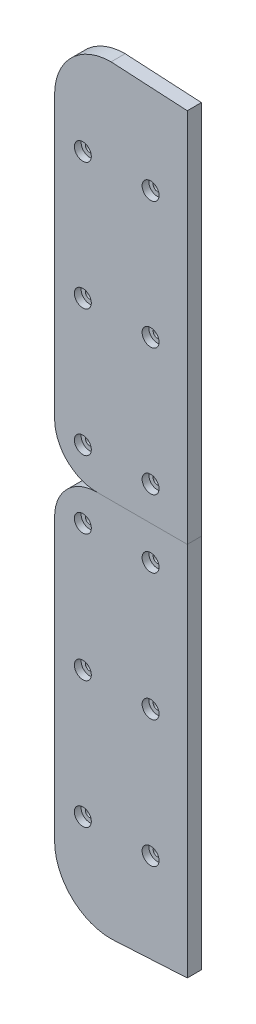
SolidWorks part; units mm, degrees
other "Folder spoin"
material "ABS PC"
ref_plane "Płaszczyzna przednia" through (0, 0, 0) normal (0, 0, 1) x (1, 0, 0)
ref_plane "Płaszczyzna górna" through (0, 0, 0) normal (0, 1, 0) x (1, 0, 0)
ref_plane "Płaszczyzna prawa" through (0, 0, 0) normal (1, 0, 0) x (0, 0, -1)
sketch "outer-wire" plane through (0, 0, 0) normal (0, 0, 1) x (1, 0, 0)
  line L0 (-24, -24.5302) -> (8, -24.5302)
  line L3 (-39, -9.5302) -> (-39, 90)
  line L13 (8, -24.5302) -> (8, 108.5046)
  line L14 (-19, 110) -> (8, 108.5046)
  arc A0 (-39, -9.5302) -> (-24, -24.5302) centre (-24, -9.5302) ccw
  arc A1 (-19, 110) -> (-39, 90) centre (-19, 90) ccw
  dimension "D2" = 20
  dimension "D1" = 15
  dimension "D20" = 39
  dimension "D21" = 110
  dimension "D22" = 47
extrude "Dodanie-wyciągnięcie1" add sketch "outer-wire" along normal blind 5 contours L0 L13 L14 A1 L3 A0
ref_plane "Płaszczyzna6" through (0, -24.5302, 0) normal (0, -1, 0) x (-1, 0, 0)
sketch "Szkic1" plane through (0, -24.5302, 0) normal (0, -1, 0) x (-1, 0, 0)
  line L0 (24, 0) -> (-8, 0) construction
  line L1 (24, -5) -> (24, 0) construction
  circle A0 centre (19, 0) radius 3.5
  dimension "D1" = 7
  dimension "D2" = 5
extrude "Wytnij-wyciągnięcie1" cut sketch "Szkic1" against normal blind 88.4
ref_plane "Płaszczyzna12" through (0, 0, 5) normal (0, 0, 1) x (1, 0, 0)
sketch "Szkic3" plane through (0, 0, 5) normal (0, 0, 1) x (1, 0, 0)
  circle A2 centre (-5, 77.5) radius 1.5
  circle A3 centre (-29, 77.5) radius 1.5
  circle A4 centre (-29, -12.5) radius 1.5
  circle A5 centre (-29, 32.5) radius 1.5
  circle A6 centre (-5, 32.5) radius 1.5
  circle A7 centre (-5, -12.5) radius 1.5
  dimension "D6" = 45
  dimension "D2" = 12.5
  dimension "D3" = 24
  dimension "D4" = 45
  dimension "D5" = 45
  dimension "D7" = 5
extrude "Wytnij-wyciągnięcie3" cut sketch "Szkic3" along direction (0, 0, 1) on the side against the normal blind 5
ref_plane "Płaszczyzna13" through (0, 0, 5) normal (0, 0, 1) x (1, 0, 0)
sketch "Szkic5" plane through (0, 0, 5) normal (0, 0, 1) x (1, 0, 0)
  circle A0 centre (-29, -12.5) radius 3
  circle A1 centre (-29, 32.5) radius 3
  circle A2 centre (-29, 77.5) radius 3
  circle A3 centre (-5, 77.5) radius 3
  circle A4 centre (-5, 32.5) radius 3
  circle A5 centre (-5, -12.5) radius 3
  dimension "D2" = 24
  dimension "D3" = 45
  dimension "D4" = 45
extrude "Wytnij-wyciągnięcie4" cut sketch "Szkic5" against normal blind 2.4 contours A0
mirror "Lustro5" about plane through (-24, -24.5302, 5) normal (0, 1, 0) of bodies 110
ref_plane "Płaszczyzna14" through (0, -114.4302, 0) normal (0, 1, 0) x (1, 0, 0)
sketch "Szkic6" plane through (0, -114.4302, 0) normal (0, 1, 0) x (1, 0, 0)
  circle A0 centre (-19, 0) radius 3.5
  dimension "D1" = 7
extrude "Wytnij-wyciągnięcie5" cut sketch "Szkic6" against normal blind 5 contours A0
ref_plane "Płaszczyzna15" through (0, -122.4302, 0) normal (0, 1, 0) x (1, 0, 0)
sketch "Szkic8" plane through (0, -122.4302, 0) normal (0, 1, 0) x (1, 0, 0)
  circle A0 centre (-19, 0) radius 3.5
  dimension "D1" = 7
extrude "Wytnij-wyciągnięcie6" cut sketch "Szkic8" against normal blind 5
sketch "Szkic9" plane through (0, -122.4302, 0) normal (0, 1, 0) x (1, 0, 0)
  line L0 (-15.5, 0) -> (-22.5, 0) construction
  circle A0 centre (-19, 0) radius 1.5
  dimension "D1" = 3
extrude "Wytnij-wyciągnięcie7" cut sketch "Szkic9" along normal blind 3
sketch "Szkic10" plane through (0, -114.4302, 0) normal (0, 1, 0) x (1, 0, 0)
  line L0 (-15.5, 0) -> (-22.5, 0) construction
  circle A0 centre (-19, 0) radius 2.85
  dimension "D1" = 5.7
extrude "Wytnij-wyciągnięcie8" cut sketch "Szkic10" along normal blind 2
sketch "Szkic11" plane through (0, 0, 0) normal (0, 0, -1) x (-1, 0, 0)
  line L1 (15.5, -114.4302) -> (22.5, -114.4302)
  line L2 (15.5, -114.4302) -> (15.5, -119.4302)
  line L3 (15.5, -119.4302) -> (22.5, -119.4302)
  line L4 (22.5, -114.4302) -> (22.5, -119.4302)
  line L5 (22.5, -122.4302) -> (15.5, -122.4302)
  line L6 (22.5, -122.4302) -> (22.5, -127.4302)
  line L7 (22.5, -127.4302) -> (15.5, -127.4302)
  line L8 (15.5, -122.4302) -> (15.5, -127.4302)
extrude "Wytnij-wyciągnięcie9" cut sketch "Szkic11" against normal blind 3.5
